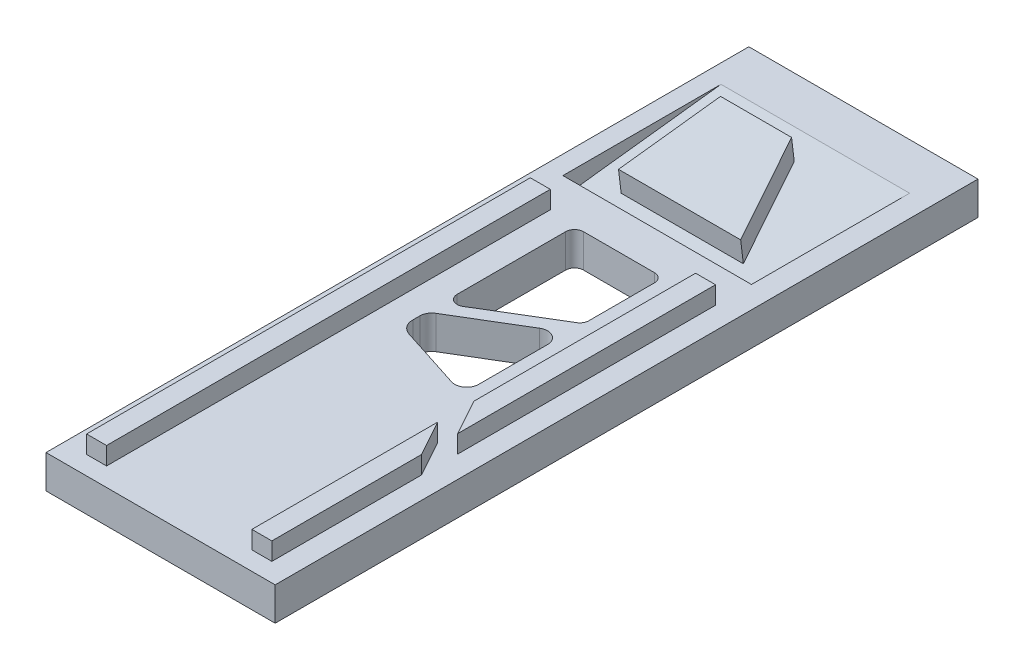
SolidWorks part; units mm, degrees
ref_plane "前视基准面" through (0, 0, 0) normal (0, 0, 1) x (1, 0, 0)
ref_plane "上视基准面" through (0, 0, 0) normal (0, 1, 0) x (1, 0, 0)
ref_plane "右视基准面" through (0, 0, 0) normal (1, 0, 0) x (0, 0, -1)
sketch "草图1" plane through (0, 0, 0) normal (0, 1, 0) x (1, 0, 0)
  line L1 (0, 0) -> (10.65, 0)
  line L2 (0, 0) -> (0, -32)
  line L3 (0, -32) -> (10.65, -32)
  line L4 (10.65, 0) -> (10.65, -32)
  dimension "D1" = 32
  dimension "D2" = 10.65
extrude "凸台-拉伸1" add sketch "草图1" along normal blind 1.5
sketch "草图3" plane through (0, 0, 0) normal (-1, 0, 0) x (0, 0, 1)
  line L0 (22.6197, 1.5) -> (29.7459, 1.5)
  line L1 (0, 1.5) -> (32, 1.5) construction
  line L2 (29.7459, 1.5) -> (22.6197, 0.65)
  line L3 (22.6197, 0.65) -> (22.6197, 1.5)
  dimension "D1" = 0.85
extrude "切除-拉伸1" cut sketch "草图3" against normal blind 8.5 from offset 1 offset against normal yes
sketch "草图4" plane through (0, 1.5, 0) normal (0, 1, 0) x (1, 0, 0)
  line L0 (5.325, 0) -> (5.325, -18.3684) construction
  line L1 (2.05, -1) -> (1.15, -1)
  line L2 (2.05, -1) -> (2.05, -21)
  line L3 (2.05, -21) -> (1.15, -21)
  line L4 (1.15, -1) -> (1.15, -21)
  line L5 (8.6, -1) -> (9.5, -1)
  line L6 (8.6, -1) -> (8.6, -21)
  line L7 (8.6, -21) -> (9.5, -21)
  line L8 (9.5, -1) -> (9.5, -21)
  line L9 (10.65, 0) -> (0, 0) construction
  line L10 (9.5, -29.7459) -> (9.5, -22.6197) construction
  dimension "D1" = 0.9
  dimension "D2" = 0.9
  dimension "D3" = 1
  dimension "D4" = 1
  dimension "D5" = 20
  dimension "D6" = 20
extrude "凸台-拉伸2" add sketch "草图4" along normal blind 0.8
sketch "草图5" plane through (0, 1.5, 0) normal (0, 1, 0) x (1, 0, 0)
  line L0 (3.25, -15.6041) -> (3.25, -20.4952)
  line L1 (3.65, -20.8952) -> (6.85, -20.8952)
  line L2 (7.25, -20.4952) -> (7.25, -17.5369)
  line L3 (7.0568, -17.1945) -> (3.8568, -15.2617)
  line L4 (5.25, -22.6197) -> (5.25, -18.0531) construction
  line L5 (9.5, -22.6197) -> (1, -22.6197) construction
  line L6 (3.5103, -14.3805) -> (6.4363, -16.1394)
  line L7 (7.25, -15.6792) -> (7.25, -12.5694)
  line L8 (6.5488, -12.0581) -> (3.7131, -12.9686)
  line L9 (3.25, -13.6037) -> (3.25, -13.9202)
  arc A0 (3.25, -15.6041) -> (3.8568, -15.2617) centre (3.65, -15.6041) cw
  arc A1 (7.25, -17.5369) -> (7.0568, -17.1945) centre (6.85, -17.5369) ccw
  arc A2 (3.65, -20.8952) -> (3.25, -20.4952) centre (3.65, -20.4952) cw
  arc A3 (6.85, -20.8952) -> (7.25, -20.4952) centre (6.85, -20.4952) ccw
  arc A4 (3.25, -13.6037) -> (3.7131, -12.9686) centre (3.917, -13.6037) cw
  arc A5 (3.25, -13.9202) -> (3.5103, -14.3805) centre (3.787, -13.9202) ccw
  arc A6 (7.25, -12.5694) -> (6.5488, -12.0581) centre (6.713, -12.5694) ccw
  arc A7 (6.4363, -16.1394) -> (7.25, -15.6792) centre (6.713, -15.6792) ccw
  point P10 (3.25, -14.8952)
  point P15 (3.25, -20.8952)
  point P18 (7.25, -20.8952)
  dimension "D3" = 0.4
  dimension "D4" = 0.4
  dimension "D5" = 0.4
  dimension "D6" = 0.4
  dimension "D7" = 0.667
  dimension "D8" = 0.537
  dimension "D9" = 0.537
  dimension "D10" = 0.537
  dimension "D1" = 4
  dimension "D2" = 6
extrude "切除-拉伸2" cut sketch "草图5" against normal blind 5.8
sketch "草图6" plane through (0, 2.3, 0) normal (0, 1, 0) x (1, 0, 0)
  line L0 (9.5, -7.7442) -> (8.6, -9.3701)
  line L1 (9.5, -21) -> (9.5, -1) construction
  line L2 (8.6, -1) -> (8.6, -21) construction
  line L3 (8.6, -9.3701) -> (8.6, -11)
  line L4 (8.6, -11) -> (9.5, -9.3741)
  line L5 (9.5, -9.3741) -> (9.5, -7.7442)
extrude "切除-拉伸3" cut sketch "草图6" against normal up to vertex (0.8 mm away)
sketch "草图7" plane through (0, -2.0193, 0.2409) normal (0, 0.993, -0.1184) x (1, 0, 0)
  line L0 (2.3084, -23.8639) -> (7.8146, -23.8639)
  line L1 (7.8146, -23.8639) -> (5.512, -28.4941)
  line L2 (5.512, -28.4941) -> (2.3084, -28.4941)
  line L3 (2.3084, -28.4941) -> (2.3084, -23.8639)
extrude "凸台-拉伸3" add sketch "草图7" along normal blind 1
sketch "草图8" plane through (0, 1.5, 0) normal (0, 1, 0) x (1, 0, 0)
  line L0 (0.16, -0.16) -> (0.16, -31.84)
  line L1 (0, 0) -> (10.65, 0)
  line L2 (0, 0) -> (0, -32)
  line L3 (0, -32) -> (10.65, -32)
  line L4 (10.65, 0) -> (10.65, -32)
  line L5 (0.16, -31.84) -> (10.49, -31.84)
  line L6 (10.49, -0.16) -> (10.49, -31.84)
  line L7 (0.16, -0.16) -> (10.49, -0.16)
  dimension "D1" = 0.16
extrude "切除-拉伸4" cut sketch "草图8" against normal blind 10
mirror "镜向1" about plane through (0, 0, 0) normal (0, 0, 1) of bodies 112
delete or keep bodies "实体-删除/保留 1" type delete bodies bodies 112
